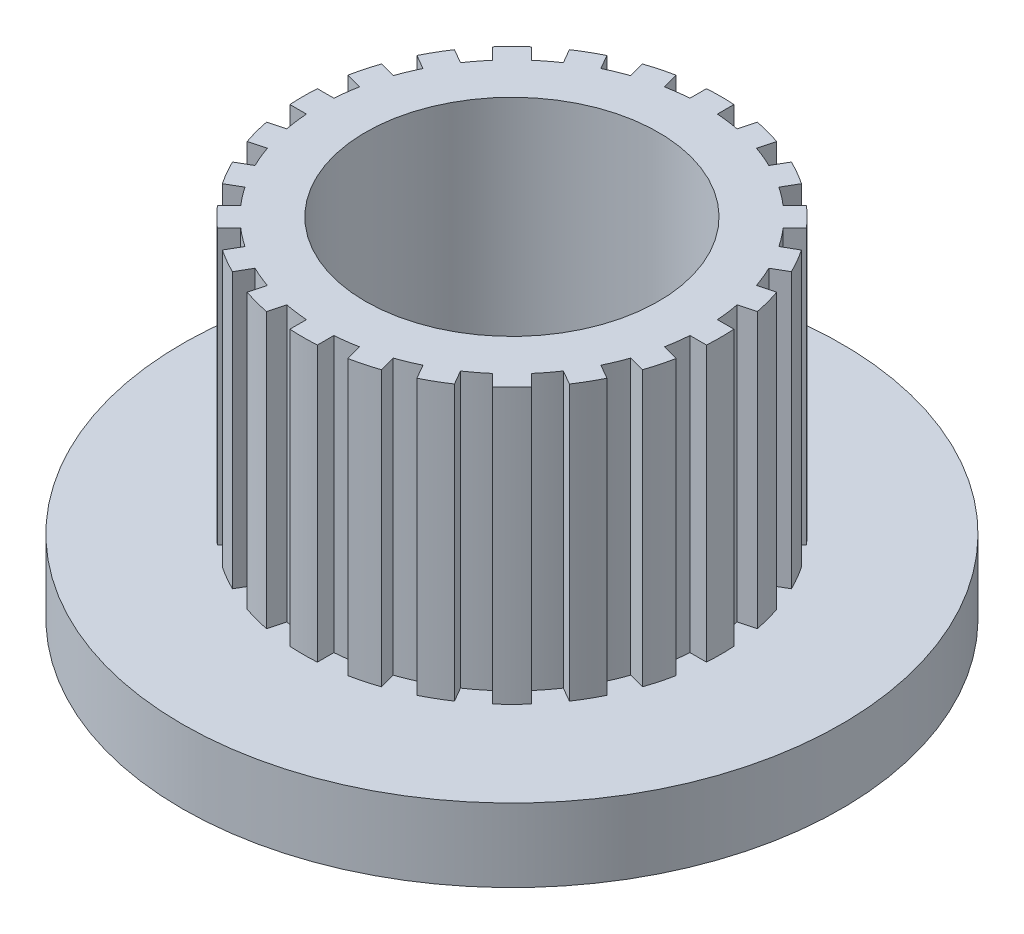
SolidWorks part; units mm, degrees
ref_plane "Front Plane" through (0, 0, 0) normal (0, 0, 1) x (1, 0, 0)
ref_plane "Top Plane" through (0, 0, 0) normal (0, 1, 0) x (1, 0, 0)
ref_plane "Right Plane" through (0, 0, 0) normal (1, 0, 0) x (0, 0, -1)
sketch "Sketch1" plane through (0, 0, 0) normal (0, 1, 0) x (1, 0, 0)
  circle A0 centre (0, 0) radius 5.25
  dimension "D1" = 10.5
extrude "Boss-Extrude1" add sketch "Sketch1" along normal blind 7.5
sketch "Sketch3" plane through (0, 0, 0) normal (1, 0, 0) x (0, 0, -1)
  line L0 (0, 0) -> (0, 12.831) construction
sketch "Sketch2" plane through (0, 0, 0) normal (0, -1, 0) x (1, 0, 0)
  line L0 (11, 0.375) -> (5, 0.375)
  line L1 (11, 0.375) -> (11, -0.375)
  line L2 (5, 0.375) -> (5, -0.375)
  line L3 (11, -0.375) -> (5, -0.375)
  line L4 (11, 0.375) -> (5, -0.375) construction
  line L5 (5, 0.375) -> (11, -0.375) construction
  line L6 (10.5281, -3.2092) -> (4.7326, -1.6563)
  line L7 (10.7222, -2.4848) -> (10.5281, -3.2092)
  line L8 (10.7222, -2.4848) -> (4.9267, -0.9319)
  line L9 (4.9267, -0.9319) -> (4.7326, -1.6563)
  line L10 (9.3388, -5.8248) -> (4.1426, -2.8248)
  line L11 (9.7138, -5.1752) -> (9.3388, -5.8248)
  line L12 (9.7138, -5.1752) -> (4.5176, -2.1752)
  line L13 (4.5176, -2.1752) -> (4.1426, -2.8248)
  line L14 (7.513, -8.0433) -> (3.2704, -3.8007)
  line L15 (8.0433, -7.513) -> (7.513, -8.0433)
  line L16 (8.0433, -7.513) -> (3.8007, -3.2704)
  line L17 (3.8007, -3.2704) -> (3.2704, -3.8007)
  line L18 (5.1752, -9.7138) -> (2.1752, -4.5176)
  line L19 (5.8248, -9.3388) -> (5.1752, -9.7138)
  line L20 (5.8248, -9.3388) -> (2.8248, -4.1426)
  line L21 (2.8248, -4.1426) -> (2.1752, -4.5176)
  line L22 (2.4848, -10.7222) -> (0.9319, -4.9267)
  line L23 (3.2092, -10.5281) -> (2.4848, -10.7222)
  line L24 (3.2092, -10.5281) -> (1.6563, -4.7326)
  line L25 (1.6563, -4.7326) -> (0.9319, -4.9267)
  line L26 (-0.375, -11) -> (-0.375, -5)
  line L27 (0.375, -11) -> (-0.375, -11)
  line L28 (0.375, -11) -> (0.375, -5)
  line L29 (0.375, -5) -> (-0.375, -5)
  line L30 (-3.2092, -10.5281) -> (-1.6563, -4.7326)
  line L31 (-2.4848, -10.7222) -> (-3.2092, -10.5281)
  line L32 (-2.4848, -10.7222) -> (-0.9319, -4.9267)
  line L33 (-0.9319, -4.9267) -> (-1.6563, -4.7326)
  line L34 (-5.8248, -9.3388) -> (-2.8248, -4.1426)
  line L35 (-5.1752, -9.7138) -> (-5.8248, -9.3388)
  line L36 (-5.1752, -9.7138) -> (-2.1752, -4.5176)
  line L37 (-2.1752, -4.5176) -> (-2.8248, -4.1426)
  line L38 (-8.0433, -7.513) -> (-3.8007, -3.2704)
  line L39 (-7.513, -8.0433) -> (-8.0433, -7.513)
  line L40 (-7.513, -8.0433) -> (-3.2704, -3.8007)
  line L41 (-3.2704, -3.8007) -> (-3.8007, -3.2704)
  line L42 (-9.7138, -5.1752) -> (-4.5176, -2.1752)
  line L43 (-9.3388, -5.8248) -> (-9.7138, -5.1752)
  line L44 (-9.3388, -5.8248) -> (-4.1426, -2.8248)
  line L45 (-4.1426, -2.8248) -> (-4.5176, -2.1752)
  line L46 (-10.7222, -2.4848) -> (-4.9267, -0.9319)
  line L47 (-10.5281, -3.2092) -> (-10.7222, -2.4848)
  line L48 (-10.5281, -3.2092) -> (-4.7326, -1.6563)
  line L49 (-4.7326, -1.6563) -> (-4.9267, -0.9319)
  line L50 (-11, 0.375) -> (-5, 0.375)
  line L51 (-11, -0.375) -> (-11, 0.375)
  line L52 (-11, -0.375) -> (-5, -0.375)
  line L53 (-5, -0.375) -> (-5, 0.375)
  line L54 (-10.5281, 3.2092) -> (-4.7326, 1.6563)
  line L55 (-10.7222, 2.4848) -> (-10.5281, 3.2092)
  line L56 (-10.7222, 2.4848) -> (-4.9267, 0.9319)
  line L57 (-4.9267, 0.9319) -> (-4.7326, 1.6563)
  line L58 (-9.3388, 5.8248) -> (-4.1426, 2.8248)
  line L59 (-9.7138, 5.1752) -> (-9.3388, 5.8248)
  line L60 (-9.7138, 5.1752) -> (-4.5176, 2.1752)
  line L61 (-4.5176, 2.1752) -> (-4.1426, 2.8248)
  line L62 (-7.513, 8.0433) -> (-3.2704, 3.8007)
  line L63 (-8.0433, 7.513) -> (-7.513, 8.0433)
  line L64 (-8.0433, 7.513) -> (-3.8007, 3.2704)
  line L65 (-3.8007, 3.2704) -> (-3.2704, 3.8007)
  line L66 (-5.1752, 9.7138) -> (-2.1752, 4.5176)
  line L67 (-5.8248, 9.3388) -> (-5.1752, 9.7138)
  line L68 (-5.8248, 9.3388) -> (-2.8248, 4.1426)
  line L69 (-2.8248, 4.1426) -> (-2.1752, 4.5176)
  line L70 (-2.4848, 10.7222) -> (-0.9319, 4.9267)
  line L71 (-3.2092, 10.5281) -> (-2.4848, 10.7222)
  line L72 (-3.2092, 10.5281) -> (-1.6563, 4.7326)
  line L73 (-1.6563, 4.7326) -> (-0.9319, 4.9267)
  line L74 (0.375, 11) -> (0.375, 5)
  line L75 (-0.375, 11) -> (0.375, 11)
  line L76 (-0.375, 11) -> (-0.375, 5)
  line L77 (-0.375, 5) -> (0.375, 5)
  line L78 (3.2092, 10.5281) -> (1.6563, 4.7326)
  line L79 (2.4848, 10.7222) -> (3.2092, 10.5281)
  line L80 (2.4848, 10.7222) -> (0.9319, 4.9267)
  line L81 (0.9319, 4.9267) -> (1.6563, 4.7326)
  line L82 (5.8248, 9.3388) -> (2.8248, 4.1426)
  line L83 (5.1752, 9.7138) -> (5.8248, 9.3388)
  line L84 (5.1752, 9.7138) -> (2.1752, 4.5176)
  line L85 (2.1752, 4.5176) -> (2.8248, 4.1426)
  line L86 (8.0433, 7.513) -> (3.8007, 3.2704)
  line L87 (7.513, 8.0433) -> (8.0433, 7.513)
  line L88 (7.513, 8.0433) -> (3.2704, 3.8007)
  line L89 (3.2704, 3.8007) -> (3.8007, 3.2704)
  line L90 (9.7138, 5.1752) -> (4.5176, 2.1752)
  line L91 (9.3388, 5.8248) -> (9.7138, 5.1752)
  line L92 (9.3388, 5.8248) -> (4.1426, 2.8248)
  line L93 (4.1426, 2.8248) -> (4.5176, 2.1752)
  line L94 (10.7222, 2.4848) -> (4.9267, 0.9319)
  line L95 (10.5281, 3.2092) -> (10.7222, 2.4848)
  line L96 (10.5281, 3.2092) -> (4.7326, 1.6563)
  line L97 (4.7326, 1.6563) -> (4.9267, 0.9319)
  point P1 (8, 0)
  point P100 (0, 0)
  dimension "D1" = 8
  dimension "D2" = 6
  dimension "D3" = 0.75
  dimension "D4" = 24
extrude "Boss-Extrude2" add sketch "Sketch2" against normal up to surface (7.5 mm away) up to face at (0, 7.5, 5.25)
sketch "Sketch5" plane through (0, 0, 0) normal (1, 0, 0) x (0, 0, -1)
  line L0 (5.7, 9) -> (15.7, 9)
  line L1 (5.7, 9) -> (5.7, -1)
  line L2 (15.7, 9) -> (15.7, -1)
  line L3 (5.7, -1) -> (15.7, -1)
  dimension "D1" = 5.7
  dimension "D2" = 10
  dimension "D3" = 10
  dimension "D4" = 1
revolve "Cut-Revolve1" cut sketch "Sketch5" angle 360 about L0
sketch "Sketch6" plane through (0, 0, 0) normal (0, 1, 0) x (1, 0, 0)
  circle A0 centre (0, 0) radius 9
  dimension "D1" = 18
extrude "Boss-Extrude3" add sketch "Sketch6" against normal blind 2
sketch "Sketch7" plane through (0, 7.5, 0) normal (0, 1, 0) x (1, 0, 0)
  circle A0 centre (0, 0) radius 4
  dimension "D1" = 8
extrude "Cut-Extrude2" cut sketch "Sketch7" against normal through all contours A0
